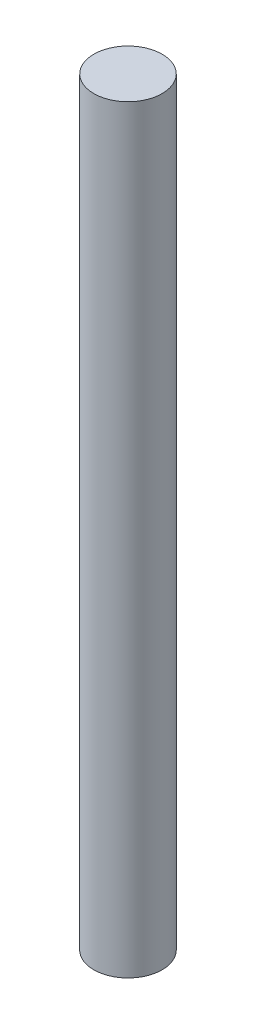
SolidWorks part; units mm, degrees
ref_plane "Front Plane" through (0, 0, 0) normal (0, 0, 1) x (1, 0, 0)
ref_plane "Top Plane" through (0, 0, 0) normal (0, 1, 0) x (1, 0, 0)
ref_plane "Right Plane" through (0, 0, 0) normal (1, 0, 0) x (0, 0, -1)
sketch "Sketch1" plane through (0, 0, 0) normal (0, 0, 1) x (1, 0, 0)
  line L0 (0, 0) -> (0, 150)
  point P6 (0, 150)
  dimension "D2" = 150
sketch "Sketch2" plane through (0, 0, 0) normal (0, 1, 0) x (1, 0, 0)
  circle A0 centre (0, 0) radius 6.75
  dimension "D1" = 13.5
sweep "Sweep1" add profiles "Sketch2" path "Sketch1"
